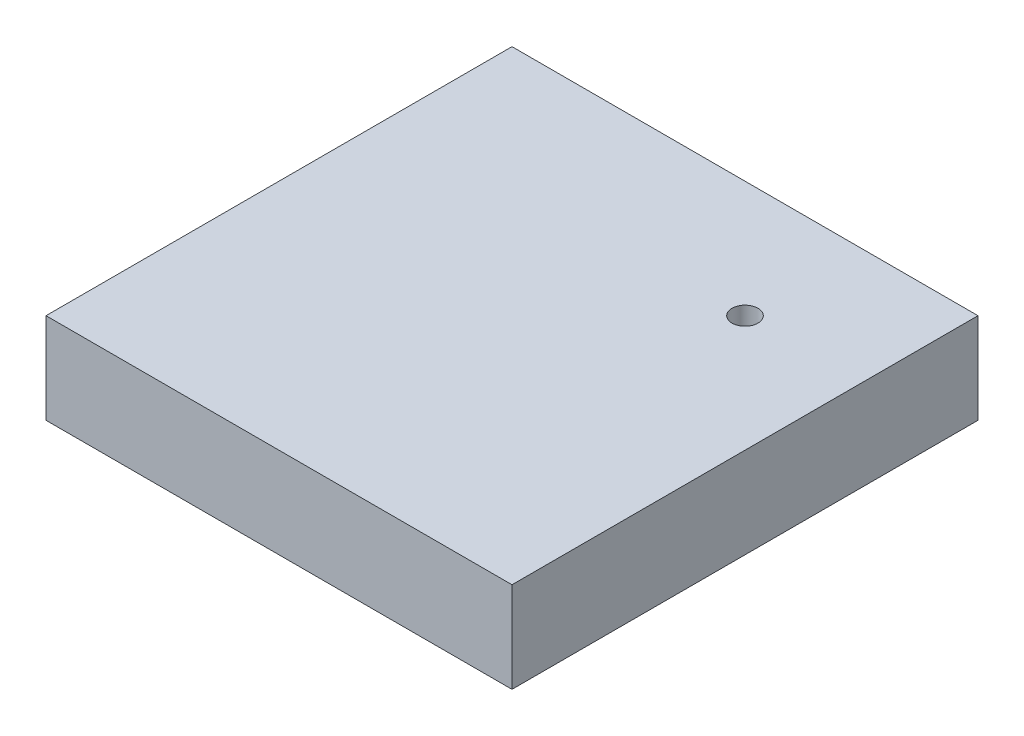
SolidWorks part; units mm, degrees
ref_plane "Front Plane" through (0, 0, 0) normal (0, 0, 1) x (1, 0, 0)
ref_plane "Top Plane" through (0, 0, 0) normal (0, 1, 0) x (1, 0, 0)
ref_plane "Right Plane" through (0, 0, 0) normal (1, 0, 0) x (0, 0, -1)
sketch "Sketch1" plane through (0, 0, 0) normal (0, 1, 0) x (1, 0, 0)
  line L1 (-57.15, -57.15) -> (57.15, -57.15)
  line L2 (-57.15, -57.15) -> (-57.15, 57.15)
  line L3 (-57.15, 57.15) -> (57.15, 57.15)
  line L4 (57.15, -57.15) -> (57.15, 57.15)
  line L5 (-57.15, -57.15) -> (57.15, 57.15) construction
  line L6 (-57.15, 57.15) -> (57.15, -57.15) construction
  point P0 (0, 0)
  dimension "D1" = 114.3
  dimension "D2" = 114.3
extrude "Boss-Extrude1" add sketch "Sketch1" along normal blind 22.225
sketch "Sketch2" plane through (0, 22.225, 0) normal (0, 1, 0) x (1, 0, 0)
  line L0 (0, 57.15) -> (0, -57.15) construction
  line L1 (57.15, 57.15) -> (-57.15, 57.15) construction
  line L2 (-57.15, -57.15) -> (57.15, -57.15) construction
  line L3 (57.15, 0) -> (-57.15, 0) construction
  line L4 (57.15, -57.15) -> (57.15, 57.15) construction
  line L5 (-57.15, 57.15) -> (-57.15, -57.15) construction
  line L6 (0, 57.15) -> (-57.15, 0) construction
  line L7 (0, 0) -> (-57.15, -57.15) construction
  line L8 (57.15, 57.15) -> (0, 0) construction
  line L9 (57.15, 0) -> (0, -57.15) construction
  point P16 (-28.575, 28.575)
  point P18 (28.575, 28.575)
  point P19 (28.575, -28.575)
  point P20 (-28.575, -28.575)
hole_wizard "1/4 (0.25) Diameter Hole1" positions "Sketch3" profile "Sketch4" hole size "1/4" standard "ANSI Inch" end condition through all
sketch "Sketch3" plane through (0, 22.225, 0) normal (0, 1, 0) x (1, 0, 0)
  point P0 (28.575, 28.575)
sketch "Sketch4" plane through (28.575, 22.225, -28.575) normal (1, 0, 0) x (0, 0, 1)
  line L0 (0, 0) -> (0, 22.225)
  line L1 (0, 22.225) -> (3.175, 22.225)
  line L2 (3.175, 22.225) -> (3.175, 0)
  line L5 (3.175, 0) -> (0, 0)
  line L11 (0, -6.35) -> (0, 107.95) construction
  dimension "Thru Hole Dia." = 6.35
  dimension "Thru Hole Depth" = 22.225
